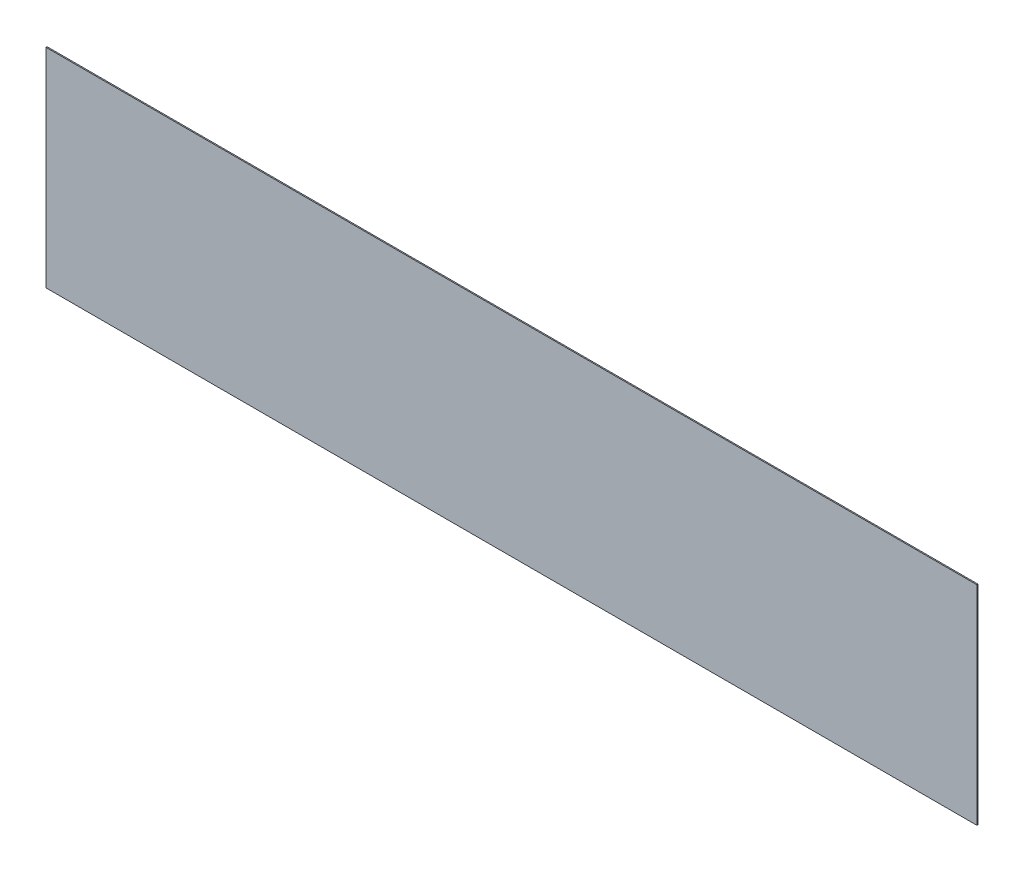
SolidWorks part; units mm, degrees
ref_plane "Front Plane" through (0, 0, 0) normal (0, 0, 1) x (1, 0, 0)
ref_plane "Top Plane" through (0, 0, 0) normal (0, 1, 0) x (1, 0, 0)
ref_plane "Right Plane" through (0, 0, 0) normal (1, 0, 0) x (0, 0, -1)
sketch "Sketch1" plane through (0, 0, 0) normal (0, 0, 1) x (1, 0, 0)
  line L1 (1333.5, 298.45) -> (-1333.5, 298.45)
  line L2 (1333.5, 298.45) -> (1333.5, -298.45)
  line L3 (1333.5, -298.45) -> (-1333.5, -298.45)
  line L4 (-1333.5, 298.45) -> (-1333.5, -298.45)
  line L5 (1333.5, 298.45) -> (-1333.5, -298.45) construction
  line L6 (1333.5, -298.45) -> (-1333.5, 298.45) construction
  point P0 (0, 0)
  dimension "D1" = 2667
  dimension "D2" = 596.9
extrude "Boss-Extrude1" add sketch "Sketch1" along normal blind 3.175
